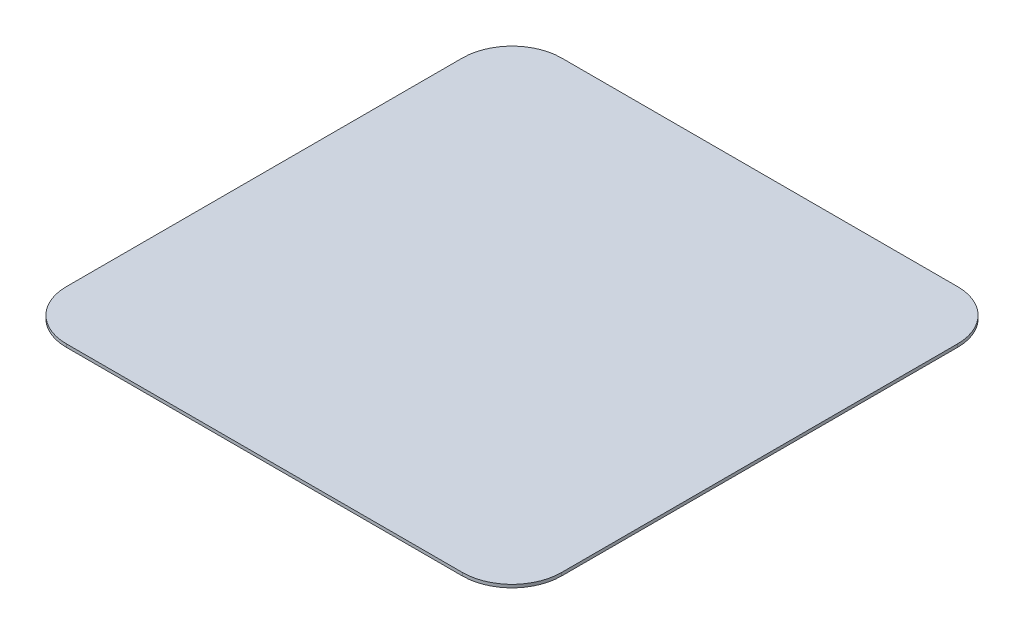
SolidWorks part; units mm, degrees
ref_plane "Front Plane" through (0, 0, 0) normal (0, 0, 1) x (1, 0, 0)
ref_plane "Top Plane" through (0, 0, 0) normal (0, 1, 0) x (1, 0, 0)
ref_plane "Right Plane" through (0, 0, 0) normal (1, 0, 0) x (0, 0, -1)
ref_plane "SheetPlane" through (0, -2.6479, 0) normal (0, -1, 0) x (-1, 0, 0)
sketch "Sketch1" plane through (0, -2.6479, 0) normal (0, -1, 0) x (-1, 0, 0)
  line L1 (50.8, 63.5) -> (-50.8, 63.5) construction
  line L2 (63.5, -50.8) -> (63.5, 50.8) construction
  line L3 (-50.8, -63.5) -> (50.8, -63.5) construction
  line L16 (-63.5, 50.8) -> (-63.5, -50.8)
  line L17 (50.8, 63.5) -> (-50.8, 63.5)
  line L18 (63.5, -50.8) -> (63.5, 50.8)
  line L19 (-50.8, -63.5) -> (50.8, -63.5)
  line L20 (-63.5, 50.8) -> (-63.5, -50.8) construction
  arc A16 (-63.5, -50.8) -> (-50.8, -63.5) centre (-50.8, -50.8) ccw
  arc A17 (-50.8, 63.5) -> (-63.5, 50.8) centre (-50.8, 50.8) ccw
  arc A18 (63.5, 50.8) -> (50.8, 63.5) centre (50.8, 50.8) ccw
  arc A19 (50.8, -63.5) -> (63.5, -50.8) centre (50.8, -50.8) ccw
extrude "MainBody" add sketch "Sketch1" along normal blind 0.7937
equation "\"SheetThickness\"= 0.03125in"
equation "\"D1@MainBody\" = \"SheetThickness\""
equation "\"SheetTolerance\"= 0.012in"
